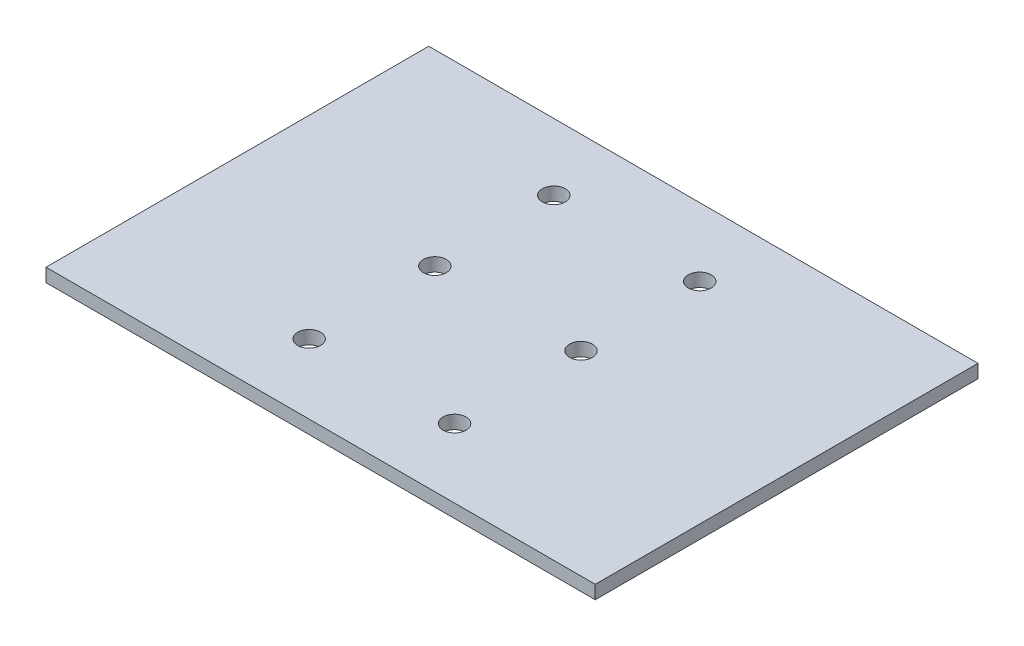
SolidWorks part; units mm, degrees
ref_plane "Front Plane" through (0, 0, 0) normal (0, 0, 1) x (1, 0, 0)
ref_plane "Top Plane" through (0, 0, 0) normal (0, 1, 0) x (1, 0, 0)
ref_plane "Right Plane" through (0, 0, 0) normal (1, 0, 0) x (0, 0, -1)
sketch "Sketch1" plane through (0, 0, 0) normal (0, 1, 0) x (1, 0, 0)
  line L0 (-26.8538, 27.9727) -> (116.6462, 27.9727)
  line L1 (116.6462, 27.9727) -> (116.6462, -72.0273)
  line L2 (116.6462, -72.0273) -> (-26.8538, -72.0273)
  line L3 (-26.8538, -72.0273) -> (-26.8538, 27.9727)
extrude "Boss-Extrude1" add sketch "Sketch1" along normal blind 3.5
hole_wizard "Ø6.0mm Dowel Hole1" positions "Sketch2" profile "Sketch3" hole size "Ø6.0" standard "ANSI Metric" end condition through all
sketch "Sketch2" plane through (237.2179, 3.5, -102.0522) normal (0, 1, 0) x (0, 0, 1)
  point P0 (156.0875, -175.3187)
sketch "Sketch3" plane through (61.8992, 3.5, 54.0353) normal (1, 0, 0) x (0, 0, 1)
  line L0 (0, 0) -> (0, 3.5)
  line L1 (0, 3.5) -> (3, 3.5)
  line L2 (3, 3.5) -> (3, 0)
  line L3 (3, 0) -> (0, 0)
  line L4 (0, -6.35) -> (0, 107.95) construction
  dimension "Thru Hole Dia." = 6
  dimension "Thru Hole Depth" = 3.5
hole_wizard "Ø6.0mm Dowel Hole2" positions "Sketch4" profile "Sketch5" hole size "Ø6.0" standard "ANSI Metric" end condition through all
sketch "Sketch4" plane through (237.2179, 3.5, -102.0522) normal (0, 1, 0) x (0, 0, 1)
  point P0 (123.0979, -175.281)
sketch "Sketch5" plane through (61.9369, 3.5, 21.0457) normal (1, 0, 0) x (0, 0, 1)
  line L0 (0, 0) -> (0, 3.5)
  line L1 (0, 3.5) -> (3, 3.5)
  line L2 (3, 3.5) -> (3, 0)
  line L3 (3, 0) -> (0, 0)
  line L4 (0, -6.35) -> (0, 107.95) construction
  dimension "Thru Hole Dia." = 6
  dimension "Thru Hole Depth" = 3.5
hole_wizard "Ø6.0mm Dowel Hole3" positions "Sketch6" profile "Sketch7" hole size "Ø6.0" standard "ANSI Metric" end condition through all
sketch "Sketch6" plane through (237.2179, 3.5, -102.0522) normal (0, 1, 0) x (0, 0, 1)
  point P0 (123.0262, -213.5355)
sketch "Sketch7" plane through (23.6824, 3.5, 20.974) normal (1, 0, 0) x (0, 0, 1)
  line L0 (0, 0) -> (0, 3.5)
  line L1 (0, 3.5) -> (3, 3.5)
  line L2 (3, 3.5) -> (3, 0)
  line L3 (3, 0) -> (0, 0)
  line L4 (0, -6.35) -> (0, 107.95) construction
  dimension "Thru Hole Dia." = 6
  dimension "Thru Hole Depth" = 3.5
hole_wizard "Ø6.0mm Dowel Hole4" positions "Sketch8" profile "Sketch9" hole size "Ø6.0" standard "ANSI Metric" end condition through all
sketch "Sketch8" plane through (237.2179, 3.5, -102.0522) normal (0, 1, 0) x (0, 0, 1)
  point P0 (155.9115, -213.4956)
sketch "Sketch9" plane through (23.7223, 3.5, 53.8594) normal (1, 0, 0) x (0, 0, 1)
  line L0 (0, 0) -> (0, 3.5)
  line L1 (0, 3.5) -> (3, 3.5)
  line L2 (3, 3.5) -> (3, 0)
  line L3 (3, 0) -> (0, 0)
  line L4 (0, -6.35) -> (0, 107.95) construction
  dimension "Thru Hole Dia." = 6
  dimension "Thru Hole Depth" = 3.5
hole_wizard "Ø6.0mm Dowel Hole5" positions "Sketch10" profile "Sketch11" hole size "Ø6.0" standard "ANSI Metric" end condition through all
sketch "Sketch10" plane through (237.2179, 3.5, -102.0522) normal (0, 1, 0) x (0, 0, 1)
  point P0 (91.4792, -213.9966)
sketch "Sketch11" plane through (23.2213, 3.5, -10.573) normal (1, 0, 0) x (0, 0, 1)
  line L0 (0, 0) -> (0, 3.5)
  line L1 (0, 3.5) -> (3, 3.5)
  line L2 (3, 3.5) -> (3, 0)
  line L3 (3, 0) -> (0, 0)
  line L4 (0, -6.35) -> (0, 107.95) construction
  dimension "Thru Hole Dia." = 6
  dimension "Thru Hole Depth" = 3.5
hole_wizard "Ø6.0mm Dowel Hole6" positions "Sketch12" profile "Sketch13" hole size "Ø6.0" standard "ANSI Metric" end condition through all
sketch "Sketch12" plane through (237.2179, 3.5, -102.0522) normal (0, 1, 0) x (0, 0, 1)
  point P0 (91.9018, -175.4545)
sketch "Sketch13" plane through (61.7634, 3.5, -10.1504) normal (1, 0, 0) x (0, 0, 1)
  line L0 (0, 0) -> (0, 3.5)
  line L1 (0, 3.5) -> (3, 3.5)
  line L2 (3, 3.5) -> (3, 0)
  line L3 (3, 0) -> (0, 0)
  line L4 (0, -6.35) -> (0, 107.95) construction
  dimension "Thru Hole Dia." = 6
  dimension "Thru Hole Depth" = 3.5
